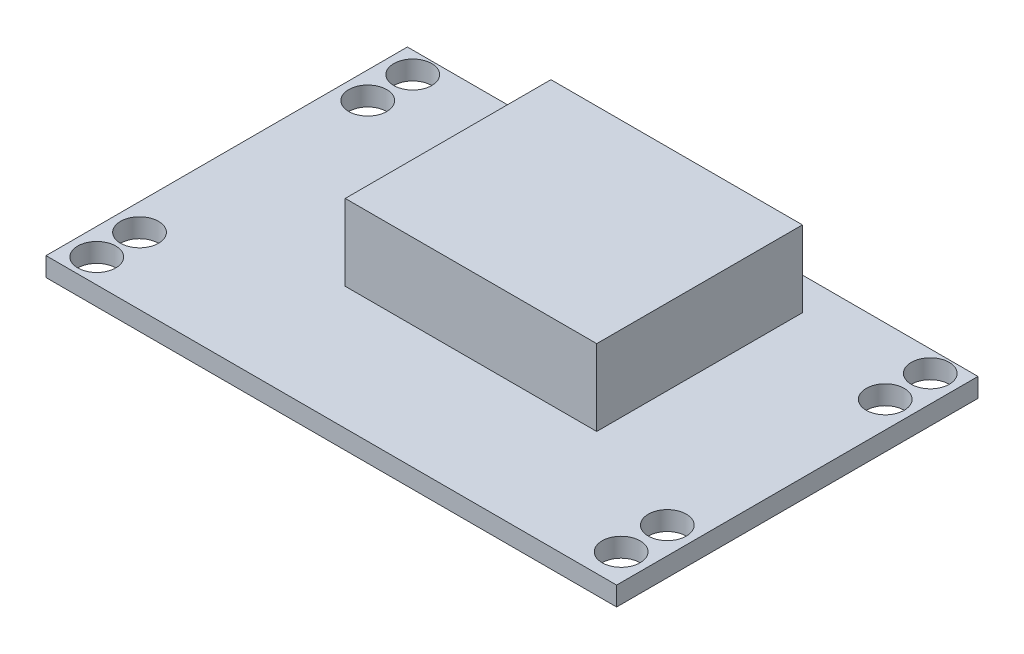
SolidWorks part; units mm, degrees
ref_plane "Front Plane" through (0, 0, 0) normal (0, 0, 1) x (1, 0, 0)
ref_plane "Top Plane" through (0, 0, 0) normal (0, 1, 0) x (1, 0, 0)
ref_plane "Right Plane" through (0, 0, 0) normal (1, 0, 0) x (0, 0, -1)
sketch "Sketch1" plane through (0, 0, 0) normal (0, 1, 0) x (1, 0, 0)
  line L1 (0, 0) -> (30, 0)
  line L2 (0, 0) -> (0, 19)
  line L3 (0, 19) -> (30, 19)
  line L4 (30, 0) -> (30, 19)
  dimension "D1" = 30
  dimension "D2" = 19
extrude "Boss-Extrude1" add sketch "Sketch1" along normal blind 1
sketch "Sketch2" plane through (0, 1, 0) normal (0, 1, 0) x (1, 0, 0)
  line L1 (9.2616, 17.2849) -> (22.4839, 17.2849)
  line L2 (9.2616, 17.2849) -> (9.2616, 6.4703)
  line L3 (9.2616, 6.4703) -> (22.4839, 6.4703)
  line L4 (22.4839, 17.2849) -> (22.4839, 6.4703)
extrude "Boss-Extrude2" add sketch "Sketch2" along normal blind 4
sketch "Sketch3" plane through (0, 1, 0) normal (0, 1, 0) x (1, 0, 0)
  circle A0 centre (1.3965, 17.8868) radius 1
  circle A1 centre (1.3965, 15.5193) radius 1
  circle A2 centre (1.3965, 3.5209) radius 1
  circle A3 centre (1.3965, 1.2737) radius 1
  circle A4 centre (28.6035, 1.6348) radius 1
  circle A5 centre (28.6035, 4.0626) radius 1
  circle A6 centre (28.6035, 17.8868) radius 1
  circle A7 centre (28.6035, 15.5193) radius 1
  dimension "D1" = 2
extrude "Cut-Extrude1" cut sketch "Sketch3" against normal through all
